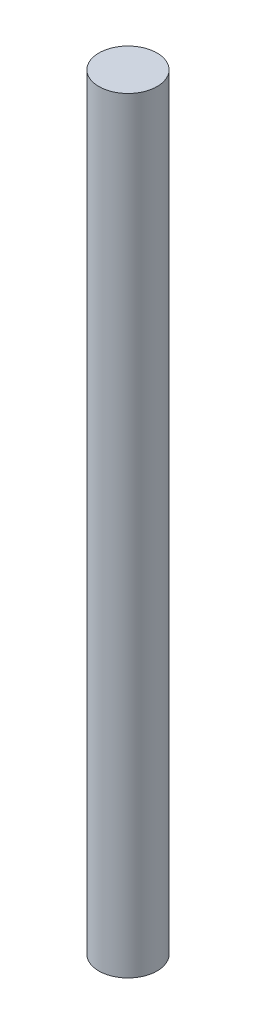
SolidWorks part; units mm, degrees
ref_plane "前视基准面" through (0, 0, 0) normal (0, 0, 1) x (1, 0, 0)
ref_plane "上视基准面" through (0, 0, 0) normal (0, 1, 0) x (1, 0, 0)
ref_plane "右视基准面" through (0, 0, 0) normal (1, 0, 0) x (0, 0, -1)
other "Configuration Table"
sketch "草图1" plane through (0, 0, 0) normal (0, 1, 0) x (1, 0, 0)
  circle A0 centre (0, 0) radius 3
  dimension "D1" = 6
extrude "凸台-拉伸1" add sketch "草图1" along normal blind 79
